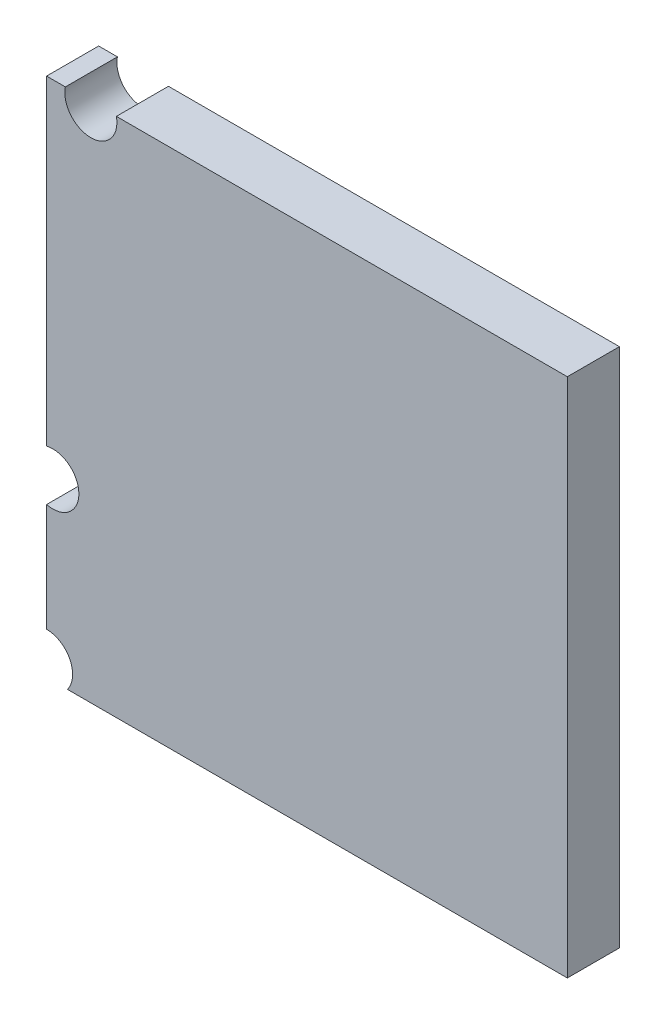
SolidWorks part; units mm, degrees
ref_plane "Спереди" through (0, 0, 0) normal (0, 0, 1) x (1, 0, 0)
ref_plane "Сверху" through (0, 0, 0) normal (0, 1, 0) x (1, 0, 0)
ref_plane "Справа" through (0, 0, 0) normal (1, 0, 0) x (0, 0, -1)
sketch "Эскиз1" plane through (0, 0, 0) normal (0, 0, 1) x (1, 0, 0)
  line L1 (0, 0) -> (100, 0)
  line L2 (0, 0) -> (0, 100)
  line L3 (0, 100) -> (100, 100)
  line L4 (100, 0) -> (100, 100)
extrude "Бобышка-Вытянуть1" add sketch "Эскиз1" along normal blind 10
sketch "Эскиз2" plane through (0, 0, 0) normal (0, 0, 1) x (1, 0, 0)
  circle A0 centre (0, 3) radius 5
extrude "Вырез-Вытянуть1" cut sketch "Эскиз2" along normal blind 10
sketch "Эскиз3" plane through (0, 0, 0) normal (0, 0, 1) x (1, 0, 0)
  circle A0 centre (1.2, 33.6) radius 5
extrude "Вырез-Вытянуть2" cut sketch "Эскиз3" along normal blind 10
sketch "Эскиз4" plane through (0, 0, 0) normal (0, 0, 1) x (1, 0, 0)
  circle A0 centre (8.5, 99) radius 5
extrude "Вырез-Вытянуть3" cut sketch "Эскиз4" along normal blind 10
